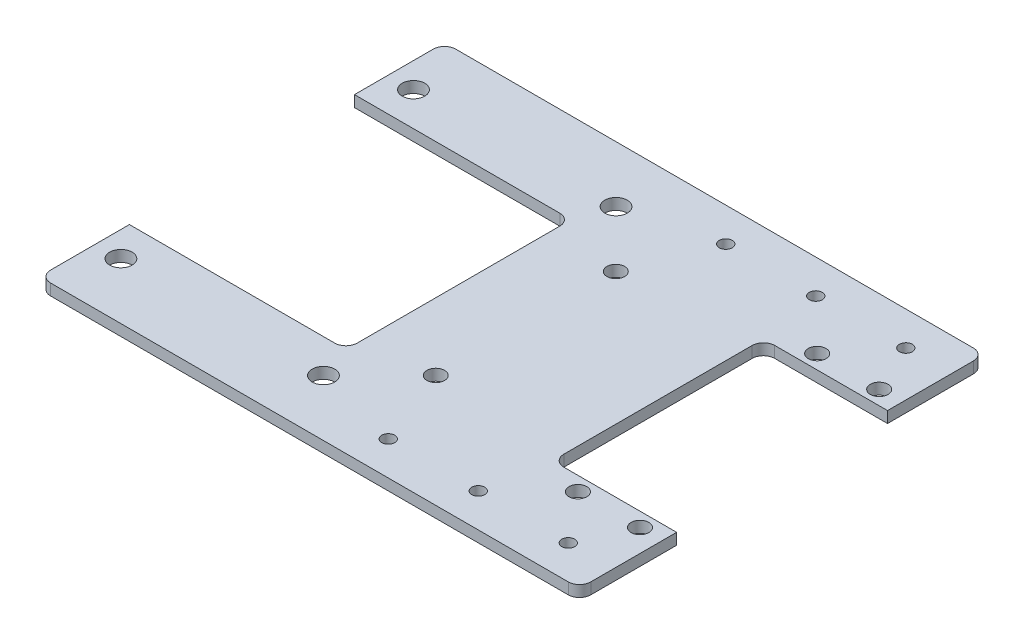
SolidWorks part; units mm, degrees
material "6061-T6 (SS)"
ref_plane "Front Plane" through (0, 0, 0) normal (0, 0, 1) x (1, 0, 0)
ref_plane "Top Plane" through (0, 0, 0) normal (0, 1, 0) x (1, 0, 0)
ref_plane "Right Plane" through (0, 0, 0) normal (1, 0, 0) x (0, 0, -1)
sketch "Sketch1" plane through (0, 0, 0) normal (0, 1, 0) x (1, 0, 0)
  line L0 (0, 0) -> (50000, 0) construction
  line L1 (121.425, 33.75) -> (138.925, 33.75) construction
  line L2 (121.425, -33.75) -> (138.925, -33.75) construction
  line L3 (130.175, 33.75) -> (130.175, 0) construction
  line L4 (130.175, 0) -> (130.175, -33.75) construction
  line L5 (-7.125, 57.15) -> (-7.125, -57.15)
  line L6 (-7.125, 57.15) -> (145.275, 57.15)
  line L7 (145.275, 57.15) -> (145.275, -57.15)
  line L8 (0, 41.275) -> (0, 0) construction
  line L9 (145.275, -57.15) -> (-7.125, -57.15)
  line L10 (0, 41.275) -> (57.15, 41.275) construction
  circle A0 centre (0, 41.275) radius 3.175
  circle A1 centre (121.425, 33.75) radius 2.5
  circle A2 centre (138.925, 33.75) radius 2.5
  circle A3 centre (138.925, -33.75) radius 2.5
  circle A4 centre (121.425, -33.75) radius 2.5
  circle A5 centre (0, -41.275) radius 3.175
  circle A10 centre (57.15, 41.275) radius 3.175
  circle A11 centre (57.15, -41.275) radius 3.175
  point P25 (152.8, 0)
  point P29 (-7.125, 0)
  dimension "D1" = 6.35
  dimension "D3" = 5
  dimension "D4" = 5
  dimension "D9" = 130.175
  dimension "D7" = 152.4
  dimension "D11" = 57.15
  dimension "D12" = 57.15
  dimension "D2" = 41.275
  dimension "D5" = 17.5
  dimension "D6" = 33.75
  dimension "D10" = 6.35
extrude "Boss-Extrude1" add sketch "Sketch1" along normal blind 3.175
sketch "Sketch2" plane through (0, 3.175, 0) normal (0, 1, 0) x (1, 0, 0)
  line L0 (145.275, 29.75) -> (110.275, 29.75)
  line L1 (-7.125, 0) -> (-7.125, -31.75)
  line L2 (145.275, 0) -> (-7.125, 0) construction
  line L3 (-7.125, 57.15) -> (-7.125, -57.15) construction
  line L4 (110.275, 29.75) -> (110.275, -29.75)
  line L5 (145.275, -29.75) -> (110.275, -29.75)
  line L6 (145.275, 29.75) -> (145.275, -29.75)
  line L7 (145.275, -57.15) -> (145.275, 57.15) construction
  line L8 (-7.125, -31.75) -> (53.975, -31.75)
  line L9 (53.975, -31.75) -> (53.975, 0)
  line L10 (53.975, 0) -> (53.975, 31.75)
  line L11 (53.975, 31.75) -> (-7.125, 31.75)
  line L12 (-7.125, 31.75) -> (-7.125, 0)
  circle A0 centre (138.925, 33.75) radius 2.5 construction
  circle A1 centre (57.15, 41.275) radius 3.175 construction
  point P13 (110.275, 0)
  dimension "D2" = 4
  dimension "D3" = 3.175
  dimension "D1" = 35
  dimension "D4" = 31.75
extrude "Cut-Extrude1" cut sketch "Sketch2" against normal up to next contours L0 L4 L5 L6 | L10 L11 L12 L1 L8 L9
fillet "Fillet1" radius 3.175 8 edges at (110.275, 1.5875, 29.75) (110.275, 1.5875, -29.75) (-7.125, 1.5875, -57.15) (-7.125, 1.5875, 57.15) (145.275, 1.5875, 57.15) (145.275, 1.5875, -57.15) (53.975, 1.5875, 31.75) (53.975, 1.5875, -31.75)
sketch "Sketch3" plane through (0, 3.175, 0) normal (0, 1, 0) x (1, 0, 0)
  line L0 (53.975, 0) -> (110.275, 0) construction
  line L1 (53.975, -28.575) -> (53.975, 28.575) construction
  line L2 (110.275, 26.575) -> (110.275, -26.575) construction
  line L3 (62.725, 57.15) -> (62.725, -57.15) construction
  line L4 (142.1, 57.15) -> (-3.95, 57.15) construction
  line L5 (-3.95, -57.15) -> (142.1, -57.15) construction
  line L6 (-7.125, 53.975) -> (-7.125, 31.75) construction
  dimension "D1" = 69.85
sketch "Sketch4" plane through (0, 3.175, 0) normal (0, 1, 0) x (1, 0, 0)
  line L0 (72.9627, -25.4) -> (72.9627, 0) construction
  line L1 (53.975, 0) -> (110.275, 0) construction
  line L2 (72.9627, 0) -> (72.9627, 25.4) construction
  circle A0 centre (72.9627, 25.4) radius 2.4892
  circle A1 centre (72.9627, -25.4) radius 2.4892
  dimension "D1" = 4.9784
  dimension "D2" = 25.4
extrude "Cut-Extrude2" cut sketch "Sketch4" against normal through all
sketch "Sketch5" plane through (0, 3.175, 0) normal (0, 1, 0) x (1, 0, 0)
  line L0 (69.075, 57.15) -> (69.075, -57.15) construction
  line L1 (142.1, 57.15) -> (-3.95, 57.15) construction
  line L2 (-3.95, -57.15) -> (142.1, -57.15) construction
  line L3 (145.275, 29.75) -> (145.275, 53.975) construction
  line L4 (145.275, -53.975) -> (145.275, -29.75) construction
  line L5 (69.075, -47.6174) -> (145.275, -47.6174) construction
  line L6 (53.975, 0) -> (110.275, 0) construction
  line L7 (53.975, -28.575) -> (53.975, 28.575) construction
  line L8 (110.275, 26.575) -> (110.275, -26.575) construction
  circle A0 centre (132.575, -47.6174) radius 1.8288
  circle A1 centre (81.775, -47.6174) radius 1.8288
  circle A2 centre (107.175, -47.6174) radius 1.8288
  circle A3 centre (107.175, 47.6174) radius 1.8288
  circle A4 centre (81.775, 47.6174) radius 1.8288
  circle A5 centre (132.575, 47.6174) radius 1.8288
  dimension "D3" = 12.7
  dimension "D4" = 25.4
  dimension "D5" = 3.6576
  dimension "D1" = 76.2
  dimension "D2" = 12.7
  dimension "D6" = 9.5326
extrude "Cut-Extrude3" cut sketch "Sketch5" against normal through all
